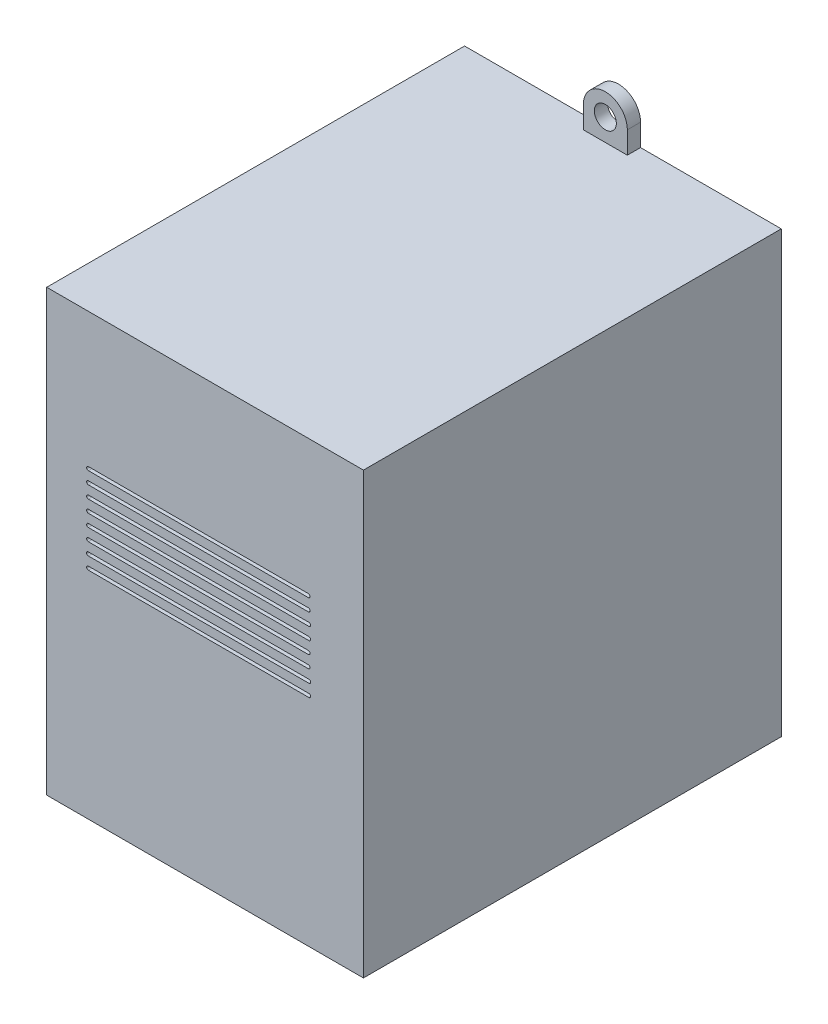
SolidWorks part; units mm, degrees
ref_plane "Plano frontal" through (0, 0, 0) normal (0, 0, 1) x (1, 0, 0)
ref_plane "Plano superior" through (0, 0, 0) normal (0, 1, 0) x (1, 0, 0)
ref_plane "Plano direito" through (0, 0, 0) normal (1, 0, 0) x (0, 0, -1)
sketch "Esboço1" plane through (0, 0, 0) normal (0, 0, 1) x (1, 0, 0)
  line L1 (-51.9084, 58.2672) -> (20.0916, 58.2672)
  line L2 (-51.9084, 58.2672) -> (-51.9084, -41.7328)
  line L3 (-51.9084, -41.7328) -> (20.0916, -41.7328)
  line L4 (20.0916, 58.2672) -> (20.0916, -41.7328)
  line L5 (-48.9084, 55.2672) -> (17.0916, 55.2672)
  line L6 (-48.9084, 55.2672) -> (-48.9084, -38.7328)
  line L7 (-48.9084, -38.7328) -> (17.0916, -38.7328)
  line L8 (17.0916, 55.2672) -> (17.0916, -38.7328)
  dimension "D1" = 100
  dimension "D2" = 72
  dimension "D3" = 3
  dimension "D4" = 3
  dimension "D5" = 3
  dimension "D6" = 3
extrude "Ressalto-extrusão1" add sketch "Esboço1" along normal blind 92
sketch "Esboço2" plane through (0, 0, 92) normal (0, 0, 1) x (1, 0, 0)
  line L1 (-51.9084, 58.2672) -> (20.0916, 58.2672)
  line L2 (-51.9084, 58.2672) -> (-51.9084, -41.7328)
  line L3 (-51.9084, -41.7328) -> (20.0916, -41.7328)
  line L4 (20.0916, 58.2672) -> (20.0916, -41.7328)
extrude "Ressalto-extrusão2" add sketch "Esboço2" along normal blind 3
sketch "Esboço3" plane through (0, 0, 95) normal (0, 0, 1) x (1, 0, 0)
  line L0 (-51.9084, 58.2672) -> (-51.9084, -41.7328) construction
  line L8 (-21.9084, 58.2672) -> (-21.9084, 63.2672)
  line L9 (20.0916, 58.2672) -> (-51.9084, 58.2672) construction
  line L10 (-11.9084, 63.2672) -> (-11.9084, 58.2672)
  line L11 (-77.0036, 8.2672) -> (99.6991, 8.2672) construction
  line L12 (-21.9084, 58.2672) -> (-11.9084, 58.2672)
  line L13 (-11.9084, -46.7328) -> (-11.9084, -41.7328)
  line L14 (-21.9084, -41.7328) -> (-21.9084, -46.7328)
  line L15 (-21.9084, -41.7328) -> (-11.9084, -41.7328)
  arc A4 (-11.9084, 63.2672) -> (-21.9084, 63.2672) centre (-16.9084, 63.2672) ccw
  circle A5 centre (-16.9084, 63.2672) radius 2.5
  circle A6 centre (-16.9084, -46.7328) radius 2.5
  arc A7 (-11.9084, -46.7328) -> (-21.9084, -46.7328) centre (-16.9084, -46.7328) cw
  dimension "D1" = 50
  dimension "D4" = 10
  dimension "D7" = 35
  dimension "D5" = 5
  dimension "D6" = 5
extrude "Ressalto-extrusão3" add sketch "Esboço3" along normal blind 3 from surface at -95 starting at face at (-15.9084, 8.2672, 0)
sketch "Esboço4" plane through (0, 0, 95) normal (0, 0, 1) x (1, 0, 0)
  line L0 (-42.4388, 27.6971) -> (7.5612, 27.6971)
  line L1 (-42.4388, 26.8971) -> (7.5612, 26.8971)
  line L2 (-42.4388, 24.8971) -> (7.5612, 24.8971)
  line L3 (-42.4388, 24.0971) -> (7.5612, 24.0971)
  line L4 (-42.4388, 27.2971) -> (-42.4388, 6.8241) construction
  line L5 (-42.4388, 22.0971) -> (7.7056, 22.0971)
  line L6 (-42.4388, 21.2971) -> (7.7056, 21.2971)
  line L7 (-42.4388, 19.2971) -> (7.7056, 19.2971)
  line L8 (-42.4388, 18.4971) -> (7.7056, 18.4971)
  line L9 (-42.4388, 16.4971) -> (7.5612, 16.4971)
  line L10 (-42.4388, 15.6971) -> (7.5612, 15.6971)
  line L11 (-42.4388, 13.6971) -> (7.5612, 13.6971)
  line L12 (-42.4388, 12.8971) -> (7.5612, 12.8971)
  line L13 (-42.4388, 10.8971) -> (7.7056, 10.8971)
  line L14 (-42.4388, 10.0971) -> (7.7056, 10.0971)
  line L15 (-42.4388, 8.0971) -> (7.7056, 8.0971)
  line L16 (-42.4388, 7.2971) -> (7.7056, 7.2971)
  arc A0 (-42.4388, 26.8971) -> (-42.4388, 27.6971) centre (-42.4388, 27.2971) cw
  arc A1 (7.5612, 26.8971) -> (7.5612, 27.6971) centre (7.5612, 27.2971) ccw
  arc A2 (-42.4388, 24.0971) -> (-42.4388, 24.8971) centre (-42.4388, 24.4971) cw
  arc A3 (7.5612, 24.0971) -> (7.5612, 24.8971) centre (7.5612, 24.4971) ccw
  arc A4 (-42.4388, 21.2971) -> (-42.4388, 22.0971) centre (-42.4388, 21.6971) cw
  arc A5 (7.7056, 21.2971) -> (7.7056, 22.0971) centre (7.7056, 21.6971) ccw
  arc A6 (-42.4388, 18.4971) -> (-42.4388, 19.2971) centre (-42.4388, 18.8971) cw
  arc A7 (7.7056, 18.4971) -> (7.7056, 19.2971) centre (7.7056, 18.8971) ccw
  arc A8 (-42.4388, 15.6971) -> (-42.4388, 16.4971) centre (-42.4388, 16.0971) cw
  arc A9 (7.5612, 15.6971) -> (7.5612, 16.4971) centre (7.5612, 16.0971) ccw
  arc A10 (-42.4388, 12.8971) -> (-42.4388, 13.6971) centre (-42.4388, 13.2971) cw
  arc A11 (7.5612, 12.8971) -> (7.5612, 13.6971) centre (7.5612, 13.2971) ccw
  arc A12 (-42.4388, 10.0971) -> (-42.4388, 10.8971) centre (-42.4388, 10.4971) cw
  arc A13 (7.7056, 10.0971) -> (7.7056, 10.8971) centre (7.7056, 10.4971) ccw
  arc A14 (-42.4388, 7.2971) -> (-42.4388, 8.0971) centre (-42.4388, 7.6971) cw
  arc A15 (7.7056, 7.2971) -> (7.7056, 8.0971) centre (7.7056, 7.6971) ccw
  point P49 (0, 0)
  dimension "D1" = 0.4
  dimension "D2" = 0.4
  dimension "D4" = 0.4
  dimension "D5" = 0.4
  dimension "D8" = 0.4
  dimension "D9" = 0.4
  dimension "D12" = 2
  dimension "D15" = 0.4
  dimension "D16" = 0.4
  dimension "D17" = 0.4
  dimension "D18" = 0.4
  dimension "D19" = 0.4
  dimension "D20" = 0.4
  dimension "D21" = 0.4
  dimension "D22" = 0.4
  dimension "D23" = 0.4
  dimension "D24" = 0.4
  dimension "D3" = 2
  dimension "D6" = 50
  dimension "D7" = 50
  dimension "D10" = 2
  dimension "D11" = 2
  dimension "D13" = 2
  dimension "2" = 2
  dimension "D14" = 2
extrude "Corte-extrusão1" cut sketch "Esboço4" against normal blind 3
sketch "Esboço5" plane through (0, 0, 0) normal (0, 0, 1) x (1, 0, 0)
  line L0 (-48.9084, 55.2672) -> (-48.9084, -38.7328) construction
  line L1 (-48.9084, 55.2672) -> (-44.9084, 55.2672)
  line L2 (-48.9084, 55.2672) -> (-48.9084, -28.7328)
  line L3 (-48.9084, -28.7328) -> (-44.9084, -28.7328)
  line L4 (-44.9084, 55.2672) -> (-44.9084, -28.7328)
  line L5 (17.0916, 55.2672) -> (-48.9084, 55.2672) construction
  line L7 (17.0916, 55.2672) -> (13.0916, 55.2672)
  line L8 (17.0916, 55.2672) -> (17.0916, -28.7328)
  line L9 (17.0916, -28.7328) -> (13.0916, -28.7328)
  line L10 (13.0916, 55.2672) -> (13.0916, -28.7328)
  point P6 (-46.9084, 55.2672)
  dimension "D1" = 84
  dimension "D2" = 4
  dimension "D3" = 4
  dimension "D4" = 84
extrude "Ressalto-extrusão4" add sketch "Esboço5" along normal blind 2 from offset 4
